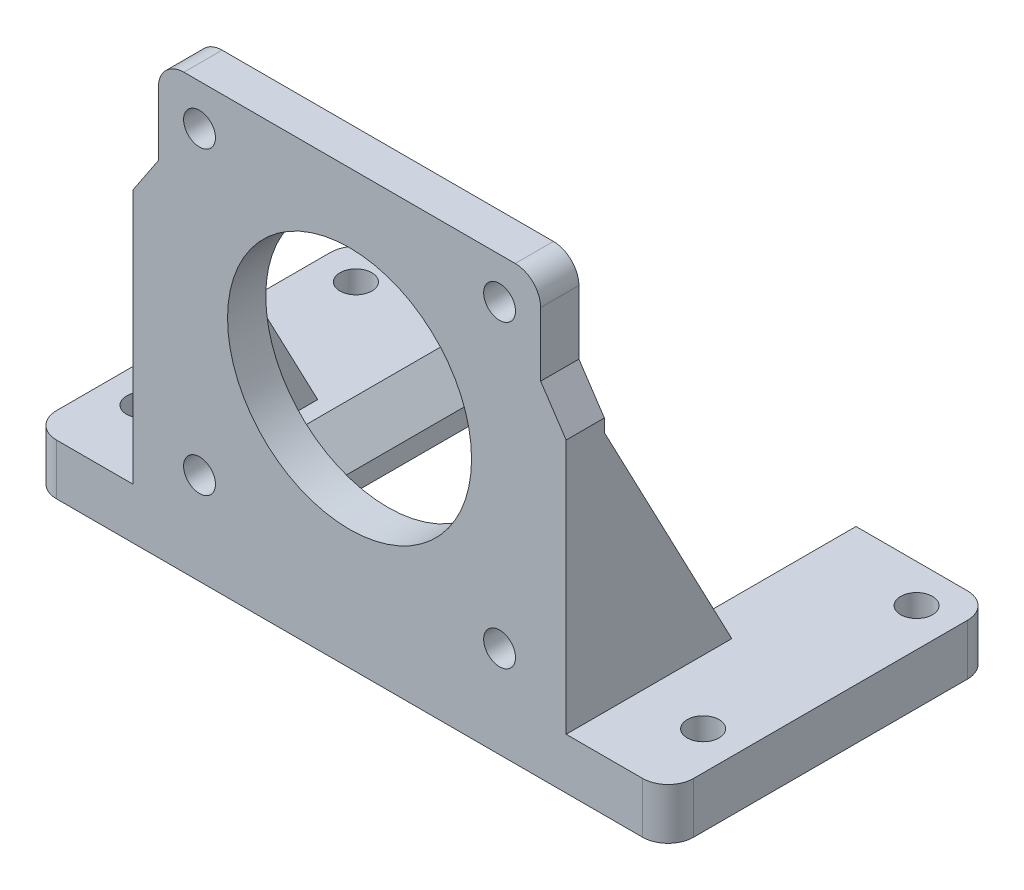
SolidWorks part; units mm, degrees
ref_plane "前视基准面" through (0, 0, 0) normal (0, 0, 1) x (1, 0, 0)
ref_plane "上视基准面" through (0, 0, 0) normal (0, 1, 0) x (1, 0, 0)
ref_plane "右视基准面" through (0, 0, 0) normal (1, 0, 0) x (0, 0, -1)
sketch "草图1" plane through (0, 0, 0) normal (0, 0, 1) x (1, 0, 0)
  line L1 (-30, 30) -> (30, 30)
  line L2 (-30, 30) -> (-30, -30)
  line L3 (-30, -30) -> (30, -30)
  line L4 (30, 30) -> (30, -30)
  line L5 (-30, 30) -> (30, -30) construction
  line L6 (-30, -30) -> (30, 30) construction
  point P0 (0, 0)
extrude "凸台-拉伸1" add sketch "草图1" along normal blind 6
sketch "草图2" plane through (0, 0, 6) normal (0, 0, 1) x (1, 0, 0)
  circle A0 centre (0, 0) radius 19.15
extrude "切除-拉伸1" cut sketch "草图2" against normal blind 6
sketch "草图3" plane through (0, 0, 6) normal (0, 0, 1) x (1, 0, 0)
  circle A0 centre (-23.55, 23.55) radius 2.5
  circle A1 centre (-23.55, -23.55) radius 2.5
  circle A2 centre (23.55, 23.55) radius 2.5
  circle A3 centre (23.55, -23.55) radius 2.5
extrude "切除-拉伸2" cut sketch "草图3" against normal blind 6
sketch "草图4" plane through (0, -30, 0) normal (0, -1, 0) x (1, 0, 0)
  line L1 (-30, 6) -> (30, 6)
  line L2 (-30, 6) -> (-30, 0)
  line L3 (-30, 0) -> (30, 0)
  line L4 (30, 6) -> (30, 0)
extrude "凸台-拉伸2" add sketch "草图4" along normal blind 8
sketch "草图5" plane through (0, 0, 0) normal (0, 0, -1) x (-1, 0, 0)
  line L0 (30, 30) -> (30, -38) construction
  line L1 (-30, -38) -> (30, -38)
  line L2 (-30, -38) -> (-30, -30)
  line L3 (-30, -30) -> (30, -30)
  line L4 (30, -38) -> (30, -30)
extrude "凸台-拉伸3" add sketch "草图5" along normal blind 45
sketch "草图6" plane through (30, 0, 0) normal (1, 0, 0) x (0, 0, -1)
  line L1 (45, -30) -> (-6, -30)
  line L2 (45, -30) -> (45, -38)
  line L3 (45, -38) -> (-6, -38)
  line L4 (-6, -30) -> (-6, -38)
extrude "凸台-拉伸4" add sketch "草图6" along normal blind 20
sketch "草图7" plane through (-30, 0, 0) normal (-1, 0, 0) x (0, 0, 1)
  line L1 (-45, -30) -> (6, -30)
  line L2 (-45, -30) -> (-45, -38)
  line L3 (-45, -38) -> (6, -38)
  line L4 (6, -30) -> (6, -38)
extrude "凸台-拉伸5" add sketch "草图7" along normal blind 20
sketch "草图8" plane through (0, 0, 0) normal (0, 0, -1) x (-1, 0, 0)
  line L0 (-30, -30) -> (-34, -30)
  line L1 (-34, -30) -> (-34, 10)
  line L5 (-30, -30) -> (-30, 30) construction
  line L6 (-30, 16) -> (-34, 10)
  line L7 (-30, 16) -> (-30, -30)
extrude "凸台-拉伸6" add sketch "草图8" against normal blind 6
sketch "草图9" plane through (0, 0, 0) normal (0, 0, -1) x (-1, 0, 0)
  line L0 (30, -30) -> (34, -30)
  line L1 (34, -30) -> (34, 10)
  line L2 (34, 10) -> (30, 16)
  line L3 (30, 30) -> (30, -30) construction
  line L4 (30, 16) -> (30, -30)
extrude "凸台-拉伸8" add sketch "草图9" against normal blind 6
sketch "草图10" plane through (34, 0, 0) normal (1, 0, 0) x (0, 0, -1)
  line L0 (0, -30) -> (20, -30)
  line L1 (0, -30) -> (0, 8)
  line L2 (0, 10) -> (0, -30) construction
  line L3 (0, 8) -> (20, -30)
extrude "凸台-拉伸10" add sketch "草图10" against normal blind 2
sketch "草图11" plane through (-34, 0, 0) normal (-1, 0, 0) x (0, 0, 1)
  line L0 (0, -30) -> (-20, -30)
  line L1 (0, -30) -> (0, 0)
  line L2 (0, 0) -> (0, 8)
  line L3 (0, -30) -> (0, 10) construction
  line L4 (0, 8) -> (-20, -30)
extrude "凸台-拉伸11" add sketch "草图11" against normal blind 2
sketch "草图12" plane through (32, 0, 0) normal (-1, 0, 0) x (0, 0, 1)
  line L0 (-20, -30) -> (0, -30)
  line L1 (0, -30) -> (0, 8)
  line L2 (0, 8) -> (-20, -30)
extrude "凸台-拉伸12" add sketch "草图12" along normal blind 1
sketch "草图13" plane through (-32, 0, 0) normal (1, 0, 0) x (0, 0, -1)
  line L0 (0, 8) -> (0, -30)
  line L1 (0, -30) -> (20, -30)
  line L2 (20, -30) -> (0, 8)
extrude "凸台-拉伸13" add sketch "草图13" along normal blind 1
sketch "草图14" plane through (0, -30, 0) normal (0, 1, 0) x (1, 0, 0)
  line L2 (17.5, 10) -> (-17.5, 10)
  line L3 (-17.5, 10) -> (-17.5, 69.5512)
  line L4 (-17.5, 69.5512) -> (17.5, 69.5512)
  line L5 (17.5, 69.5512) -> (17.5, 10)
  point P9 (17.5, 10)
extrude "切除-拉伸3" cut sketch "草图14" against normal blind 10
sketch "草图15" plane through (0, -30, 0) normal (0, 1, 0) x (1, 0, 0)
  circle A0 centre (-44, 39) radius 2.5
  circle A1 centre (-44, 5.5) radius 2.5
  circle A2 centre (44, 5.5) radius 2.5
  circle A3 centre (44, 39) radius 2.5
extrude "切除-拉伸4" cut sketch "草图15" against normal blind 10
sketch "草图16" plane through (17.5, 0, 0) normal (-1, 0, 0) x (0, 0, 1)
  line L1 (-45, -30) -> (-10, -30)
  line L2 (-45, -30) -> (-45, -38)
  line L3 (-45, -38) -> (-10, -38)
  line L4 (-10, -30) -> (-10, -38)
extrude "切除-拉伸6" cut sketch "草图16" against normal blind 6
sketch "草图17" plane through (-17.5, 0, 0) normal (1, 0, 0) x (0, 0, -1)
  line L1 (10, -30) -> (45, -30)
  line L2 (10, -30) -> (10, -38)
  line L3 (10, -38) -> (45, -38)
  line L4 (45, -30) -> (45, -38)
extrude "切除-拉伸7" cut sketch "草图17" against normal blind 6
chamfer "倒角3" distance 5 angle 45 1 edges at (23.5, -30, -27.5)
chamfer "倒角4" distance 5 angle 45 1 edges at (-23.5, -30, -27.5)
fillet "圆角2" radius 4 1 edges at (30, 30, 3)
fillet "圆角3" radius 4 1 edges at (-30, 30, 3)
fillet "圆角4" radius 4 1 edges at (50, -34, -45)
fillet "圆角5" radius 4 1 edges at (-50, -34, -45)
fillet "圆角6" radius 4 1 edges at (-50, -34, 6)
fillet "圆角7" radius 4 1 edges at (50, -34, 6)
